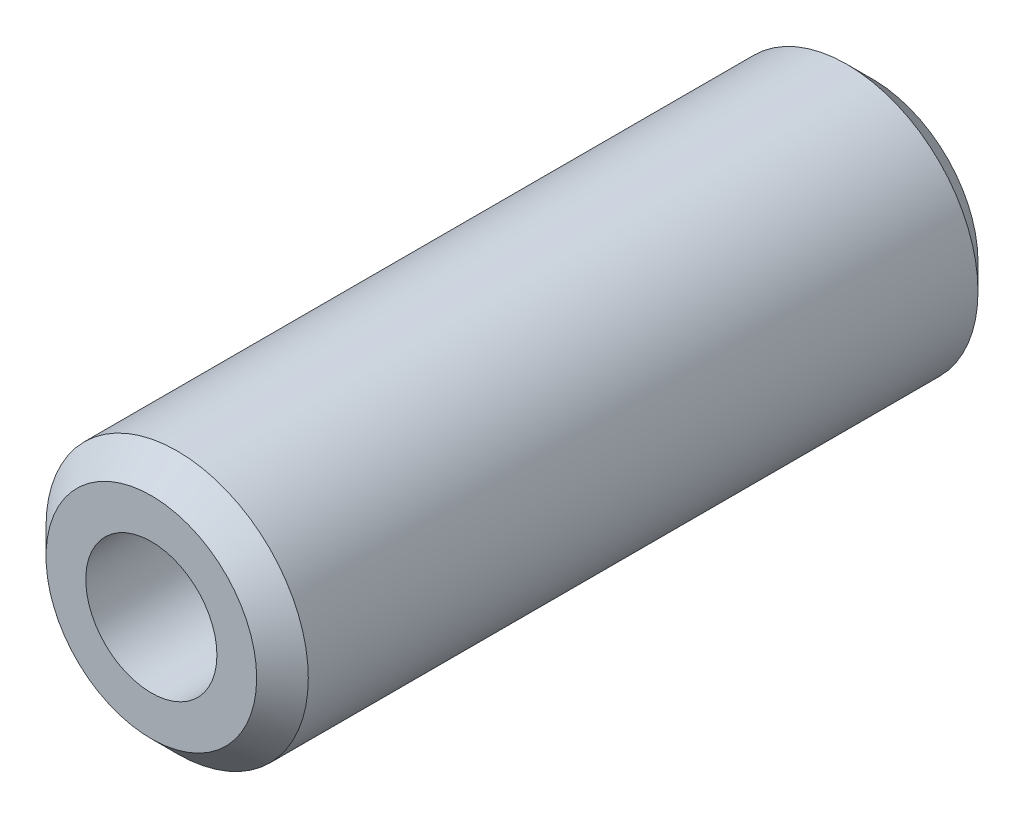
SolidWorks part; units mm, degrees
ref_plane "Front Plane" through (0, 0, 0) normal (0, 0, 1) x (1, 0, 0)
ref_plane "Top Plane" through (0, 0, 0) normal (0, 1, 0) x (1, 0, 0)
ref_plane "Right Plane" through (0, 0, 0) normal (1, 0, 0) x (0, 0, -1)
sketch "Sketch1" plane through (0, 0, 0) normal (0, 0, 1) x (1, 0, 0)
  circle A0 centre (0, 0) radius 12.7
  circle A1 centre (0, 0) radius 6.35
  dimension "D1" = 25.4
  dimension "D2" = 12.7
extrude "Boss-Extrude1" add sketch "Sketch1" along normal mid plane 69.85
chamfer "Chamfer1" distance 2.5 angle 45 2 edges at (12.7, 0, -34.925) (12.7, 0, 34.925)
